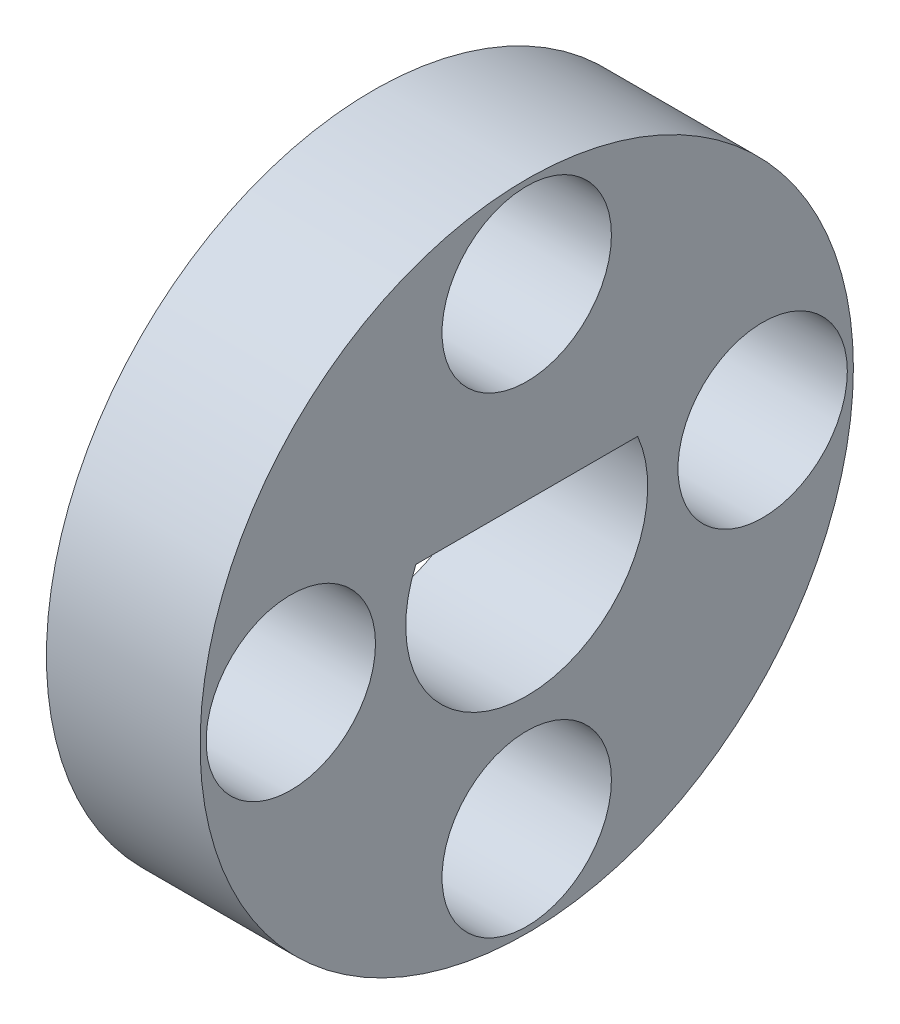
SolidWorks part; units mm, degrees
ref_plane "Front Plane" through (0, 0, 0) normal (0, 0, 1) x (1, 0, 0)
ref_plane "Top Plane" through (0, 0, 0) normal (0, 1, 0) x (1, 0, 0)
ref_plane "Right Plane" through (0, 0, 0) normal (1, 0, 0) x (0, 0, -1)
sketch "Sketch1" plane through (0, 0, 0) normal (1, 0, 0) x (0, 0, -1)
  line L0 (0, 0) -> (-13.5, 0) construction
  line L1 (4.5826, 2) -> (-4.5826, 2)
  line L2 (-8.3703, 5) -> (-12.5399, 5) construction
  circle A0 centre (0, 0) radius 13.5
  circle A1 centre (0, 0) radius 9.75 construction
  circle A2 centre (-9.75, 0) radius 3.5
  circle A3 centre (0, 9.75) radius 3.5
  circle A4 centre (9.75, 0) radius 3.5
  circle A5 centre (0, -9.75) radius 3.5
  arc A6 (-4.5826, 2) -> (4.5826, 2) centre (0, 0) ccw
  point P16 (0, 0)
  dimension "D1" = 27
  dimension "D2" = 19.5
  dimension "D3" = 7
  dimension "D5" = 10
  dimension "D6" = 3
  dimension "D4" = 4
extrude "Boss-Extrude1" add sketch "Sketch1" along normal blind 6.35
